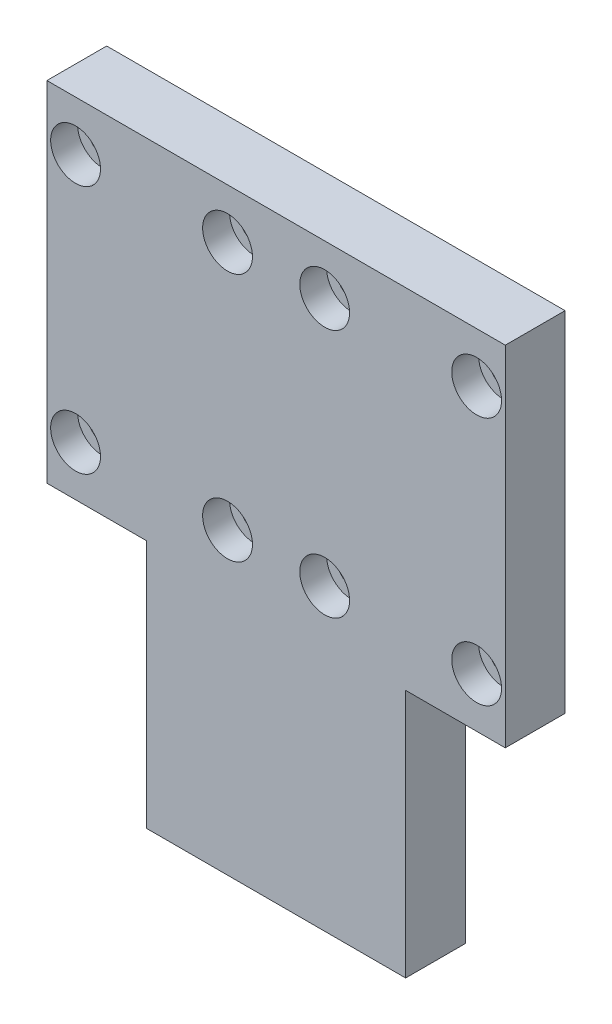
SolidWorks part; units mm, degrees
material "HDPE-green"
ref_plane "Front Plane" through (0, 0, 0) normal (0, 0, 1) x (1, 0, 0)
ref_plane "Top Plane" through (0, 0, 0) normal (0, 1, 0) x (1, 0, 0)
ref_plane "Right Plane" through (0, 0, 0) normal (1, 0, 0) x (0, 0, -1)
sketch "Sketch1" plane through (0, 0, 0) normal (0, 0, 1) x (1, 0, 0)
  line L1 (46, -60) -> (-46, -60)
  line L2 (46, -60) -> (46, 60)
  line L3 (46, 60) -> (-46, 60)
  line L4 (-46, -60) -> (-46, 60)
  line L5 (46, -60) -> (-46, 60) construction
  line L6 (46, 60) -> (-46, -60) construction
  point P0 (0, 0)
  dimension "D1" = 92
  dimension "D2" = 120
extrude "Boss-Extrude1" add sketch "Sketch1" along normal blind 12
hole_wizard "CBORE for M5 Hex Socket Head Cap Screw1" positions "Sketch3" profile "Sketch2" counterbore size "M5" standard "ISO" end condition through all
sketch "Sketch3" plane through (0, 0, 12) normal (0, 0, 1) x (1, 0, 0)
  line L0 (-40.25, 24.5934) -> (-40.25, -60) construction
  line L2 (-9.75, 24.5934) -> (-9.75, -60) construction
  line L5 (-5.4995, 50) -> (-43.2821, 50) construction
  line L8 (-41.3929, 0) -> (-2.8232, 0) construction
  line L11 (-46, -60) -> (46, -60) construction
  line L12 (46, 60) -> (-46, 60) construction
  point P0 (-40.25, 50)
  point P46 (-9.75, 50)
  point P56 (-9.75, 0)
  point P59 (0, 60)
  point P63 (-40.25, 0)
  dimension "D1" = 30.5
  dimension "D2" = 50
  dimension "D3" = 9.75
  dimension "D4" = 10
sketch "Sketch2" plane through (-40.25, 50, 12) normal (1, 0, 0) x (0, -1, 0)
  line L0 (0, 0) -> (0, 12)
  line L1 (0, 12) -> (2.75, 12)
  line L3 (2.75, 12) -> (2.75, 5.4)
  line L4 (2.75, 5.4) -> (5, 5.4)
  line L5 (5, 5.4) -> (5, 0)
  line L7 (5, 0) -> (0, 0)
  line L11 (0, -6.35) -> (0, 107.95) construction
  dimension "Thru Hole Dia." = 5.5
  dimension "Thru Hole Depth" = 12
  dimension "C'Bore Dia." = 10
  dimension "C'Bore Depth" = 5.4
mirror "Mirror1" about plane through (0, 0, 0) normal (1, 0, 0) of "CBORE for M5 Hex Socket Head Cap Screw1"
sketch "Sketch4" plane through (0, 0, 12) normal (0, 0, 1) x (1, 0, 0)
  line L0 (-46, 60) -> (-46, -60) construction
  line L1 (-46, -10) -> (-26, -10)
  line L2 (-46, -10) -> (-46, -60)
  line L3 (-46, -60) -> (-26, -60)
  line L4 (-26, -10) -> (-26, -60)
  circle A0 centre (-40.25, 0) radius 5 construction
  dimension "D1" = 10
  dimension "D3" = 20
extrude "Cut-Extrude1" cut sketch "Sketch4" against normal up to next
mirror "Mirror2" about plane through (0, 0, 0) normal (1, 0, 0) of "Cut-Extrude1"
